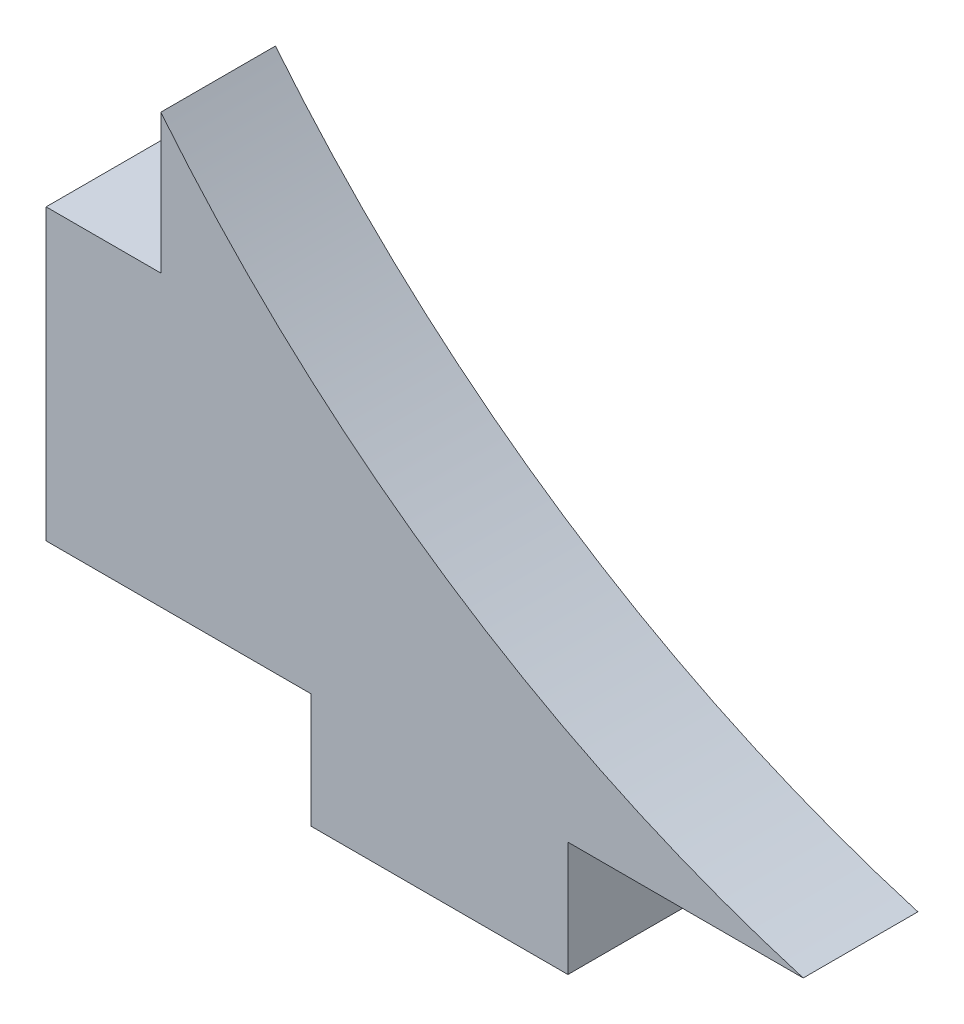
SolidWorks part; units mm, degrees
ref_plane "Front Plane" through (0, 0, 0) normal (0, 0, 1) x (1, 0, 0)
ref_plane "Top Plane" through (0, 0, 0) normal (0, 1, 0) x (1, 0, 0)
ref_plane "Right Plane" through (0, 0, 0) normal (1, 0, 0) x (0, 0, -1)
sketch "Model" plane through (0, 0, 0) normal (0, 0, 1) x (1, 0, 0)
  line L0 (-6, 5.35) -> (-18.35, 5.35)
  line L2 (-6, 5.35) -> (-6, 0)
  line L3 (-6, 0) -> (6, 0)
  line L4 (6, 5.35) -> (6, 0)
  line L5 (16.98, 5.35) -> (6, 5.35)
  line L6 (16.98, 5.35) -> (16.98, 4.7457)
  line L8 (-18.35, 5.35) -> (-18.35, 18.85)
  line L11 (-18.35, 18.85) -> (-13, 18.85)
  line L12 (-13, 25.35) -> (-13, 18.85)
  arc A0 (-13, 25.35) -> (16.98, 5.35) centre (34.0614, 63.4251) ccw
  dimension "D18" = 60.535
  dimension "D2" = 35.33
  dimension "D4" = 5.35
  dimension "D6" = 12
  dimension "D8" = 20
  dimension "D10" = 5.35
  dimension "D12" = 13.5
  dimension "D16" = 12.35
extrude "Boss-Extrude1" add sketch "Model" along normal blind 5.35 contours A0 L12 L11 L8 L0 L2 L3 L4 L5
equation "\"mdfthick\"=5.35"
equation "\"D4@Model\"=\"mdfthick\""
equation "\"D10@Model\"=\"mdfthick\""
equation "\"D1@Boss-Extrude1\"=\"mdfthick\""
